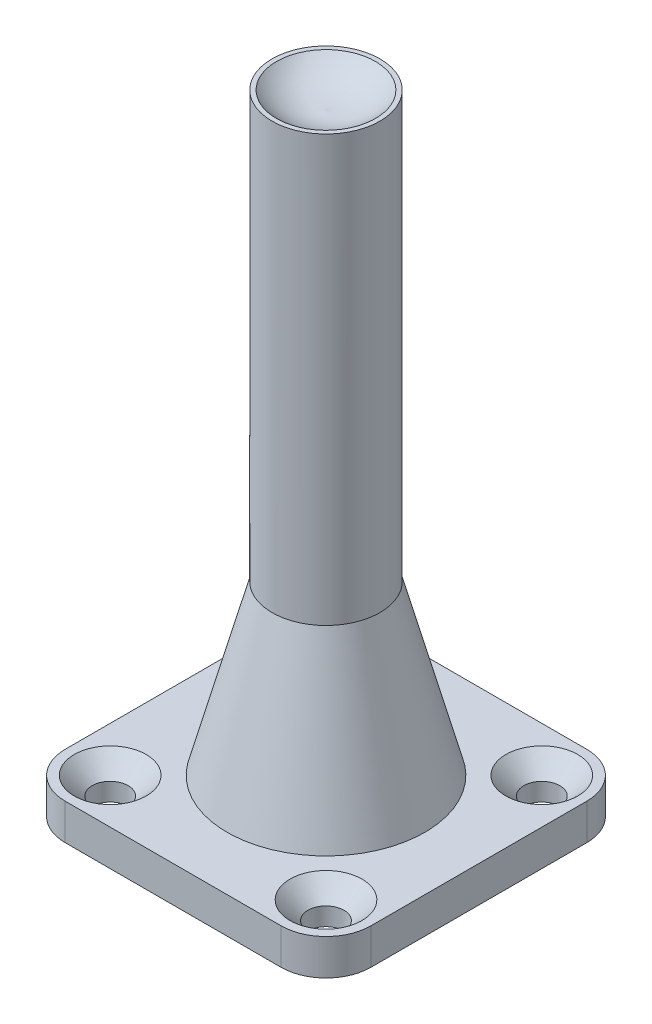
SolidWorks part; units mm, degrees
ref_plane "Спереди" through (0, 0, 0) normal (0, 0, 1) x (1, 0, 0)
ref_plane "Сверху" through (0, 0, 0) normal (0, 1, 0) x (1, 0, 0)
ref_plane "Справа" through (0, 0, 0) normal (1, 0, 0) x (0, 0, -1)
sketch "Эскиз1" plane through (0, 0, 0) normal (0, 1, 0) x (1, 0, 0)
  line L1 (-17, -17) -> (17, -17)
  line L2 (-17, -17) -> (-17, 17)
  line L3 (-17, 17) -> (17, 17)
  line L4 (17, -17) -> (17, 17)
  line L5 (0, 17) -> (0, -17) construction
  line L6 (-17, 0) -> (17, 0) construction
  line L7 (-12, -12) -> (12, -12) construction
  line L8 (-12, -12) -> (-12, 12) construction
  line L9 (-12, 12) -> (12, 12) construction
  line L10 (12, -12) -> (12, 12) construction
  line L11 (0, 12) -> (0, -12) construction
  line L12 (-12, 0) -> (12, 0) construction
  circle A0 centre (-12, 12) radius 2
  circle A1 centre (12, 12) radius 2
  circle A2 centre (12, -12) radius 2
  circle A3 centre (-12, -12) radius 2
  point P0 (0, 0)
  point P4 (0, 0)
  dimension "D5" = 4
  dimension "D1" = 34
  dimension "D3" = 24
  dimension "D4" = 24
extrude "Бобышка-Вытянуть1" add sketch "Эскиз1" along normal blind 4
fillet "Скругление1" radius 5 4 edges at (17, 2, 17) (-17, 2, -17) (17, 2, -17) (-17, 2, 17)
sketch "Эскиз2" plane through (0, 4, 0) normal (0, 1, 0) x (1, 0, 0)
  circle A0 centre (0, 0) radius 6
  dimension "D1" = 12
extrude "Бобышка-Вытянуть2" add sketch "Эскиз2" along normal blind 66
ref_plane "Плоскость1" through (0, 0, 0) normal (0, 0, 1) x (1, 0, 0)
sketch "Эскиз7" plane through (0, 0, 0) normal (0, 0, 1) x (1, 0, 0)
  line L0 (0, 82.4047) -> (0, 68) construction
  line L1 (0, 68) -> (9.0963, 68) construction
  line L2 (6, 70) -> (-6, 70) construction
  line L3 (5.5, 70) -> (0, 70)
  line L4 (0, 70) -> (0, 68)
  arc A0 (0, 68) -> (0.0893, 68) centre (0.0447, 68) ccw
  arc A1 (5.5, 70) -> (0, 68) centre (0.6855, 74.6775) cw
  dimension "D1" = 2
  dimension "D2" = 5.5
revolve "Вырез-Повернуть3" cut sketch "Эскиз7" angle 360 about L0
chamfer "Фаска1" distance 5 angle 75 1 edges at (0, 4, 6)
sketch "Эскиз5" plane through (0, 0, 0) normal (0, -1, 0) x (1, 0, 0)
  line L1 (-16.5147, -16.1651) -> (16.5147, -16.1651)
  line L2 (-16.5147, -16.1651) -> (-16.5147, 16.1651)
  line L3 (-16.5147, 16.1651) -> (16.5147, 16.1651)
  line L4 (16.5147, -16.1651) -> (16.5147, 16.1651)
  line L5 (0, 16.1651) -> (0, -16.1651) construction
  line L6 (-16.5147, 0) -> (16.5147, 0) construction
  point P0 (0, 0)
extrude "Вырез-Вытянуть2" [suppressed] cut sketch "Эскиз5" against normal blind 70
chamfer "Фаска2" distance 2 angle 45 4 edges at (-12, 4, 14) (12, 4, 14) (-12, 4, -10) (12, 4, -10)
